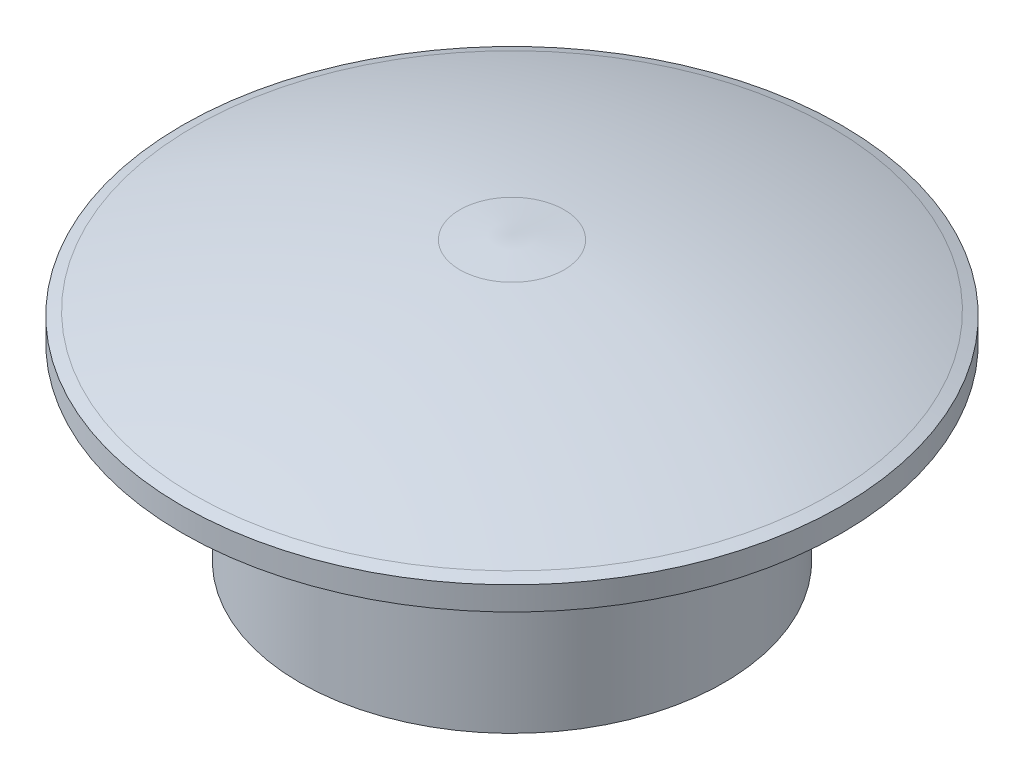
SolidWorks part; units mm, degrees
material "ABS PC"
ref_plane "Front Plane" through (0, 0, 0) normal (0, 0, 1) x (1, 0, 0)
ref_plane "Top Plane" through (0, 0, 0) normal (0, 1, 0) x (1, 0, 0)
ref_plane "Right Plane" through (0, 0, 0) normal (1, 0, 0) x (0, 0, -1)
sketch "Sketch1" plane through (0, 0, 0) normal (0, 0, 1) x (1, 0, 0)
  line L0 (0, 6) -> (0, 0) construction
  line L1 (0, 0) -> (4.5, 0)
  line L2 (4.5, 0) -> (4.5, 4)
  line L3 (4.5, 4) -> (7, 4)
  line L4 (7, 4) -> (7, 4.5)
  line L5 (0, 0) -> (0, 6)
  line L6 (7, 4.5) -> (4.0214, 5.6185)
  line L7 (4.0214, 5.6185) -> (0, 6)
  dimension "D1" = 6
  dimension "D2" = 4.5
  dimension "D3" = 7
  dimension "D4" = 0.5
  dimension "D5" = 4
revolve "Revolve3" add sketch "Sketch1" angle 360 about L0
fillet "Fillet1" radius 22 1 edges at (0, 5.6185, 4.0214)
shell "Shell1" thickness 0.25
